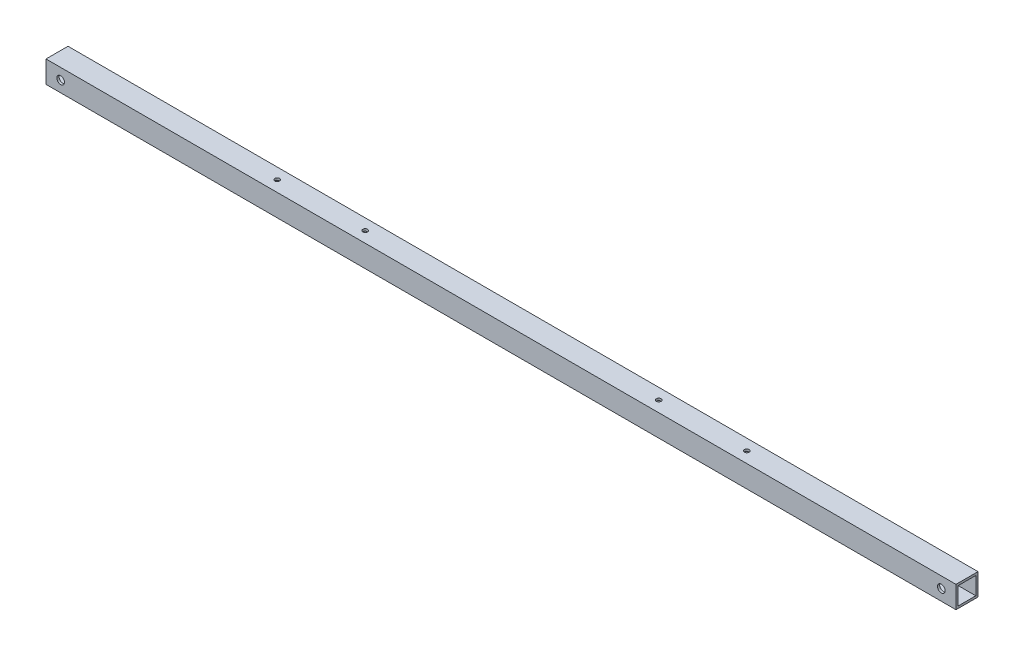
SolidWorks part; units mm, degrees
ref_plane "正面" through (0, 0, 0) normal (0, 0, 1) x (1, 0, 0)
ref_plane "平面" through (0, 0, 0) normal (0, 1, 0) x (1, 0, 0)
ref_plane "右側面" through (0, 0, 0) normal (1, 0, 0) x (0, 0, -1)
sketch "ｽｹｯﾁ2" plane through (0, 0, 0) normal (0, 0, 1) x (1, 0, 0)
  line L0 (0, 7.5) -> (620, 7.5) construction
  line L1 (0, 0) -> (620, 0)
  line L2 (0, 0) -> (0, 15)
  line L3 (0, 15) -> (620, 15)
  line L4 (620, 0) -> (620, 15)
  circle A0 centre (10, 7.5) radius 2.6
  circle A1 centre (610, 7.5) radius 2.6
  dimension "D1" = 5.2
  dimension "D2" = 10
  dimension "D3" = 10
  dimension "D5" = 600
  dimension "D4" = 15
extrude "ﾎﾞｽ - 押し出し1" add sketch "ｽｹｯﾁ2" along normal blind 15
sketch "ｽｹｯﾁ3" plane through (0, 0, 0) normal (-1, 0, 0) x (0, 0, 1)
  line L8 (1.5, 13.5) -> (1.5, 1.5)
  line L9 (1.5, 1.5) -> (13.5, 1.5)
  line L10 (13.5, 1.5) -> (13.5, 13.5)
  line L11 (13.5, 13.5) -> (1.5, 13.5)
  line L12 (1.5, 13.5) -> (1.5, 1.5)
  line L13 (1.5, 1.5) -> (13.5, 1.5)
  line L14 (13.5, 1.5) -> (13.5, 13.5)
  line L15 (13.5, 13.5) -> (1.5, 13.5)
  dimension "D1" = 1.5
extrude "ｶｯﾄ - 押し出し1" cut sketch "ｽｹｯﾁ3" against normal through all
sketch "ｽｹｯﾁ4" plane through (0, 15, 0) normal (0, 1, 0) x (1, 0, 0)
  line L0 (620, -7.5) -> (0, -7.5) construction
  line L1 (620, -15) -> (620, 0) construction
  line L2 (0, -15) -> (0, 0) construction
  line L3 (210, -7.5) -> (410, -7.5) construction
  circle A4 centre (470, -7.5) radius 1.6
  circle A5 centre (410, -7.5) radius 1.6
  circle A6 centre (150, -7.5) radius 1.6
  circle A7 centre (210, -7.5) radius 1.6
  point P8 (310, -7.5)
  dimension "D1" = 100
  dimension "D2" = 3.2
  dimension "D7" = 60
  dimension "D8" = 60
extrude "ｶｯﾄ - 押し出し2" cut sketch "ｽｹｯﾁ4" against normal through all
